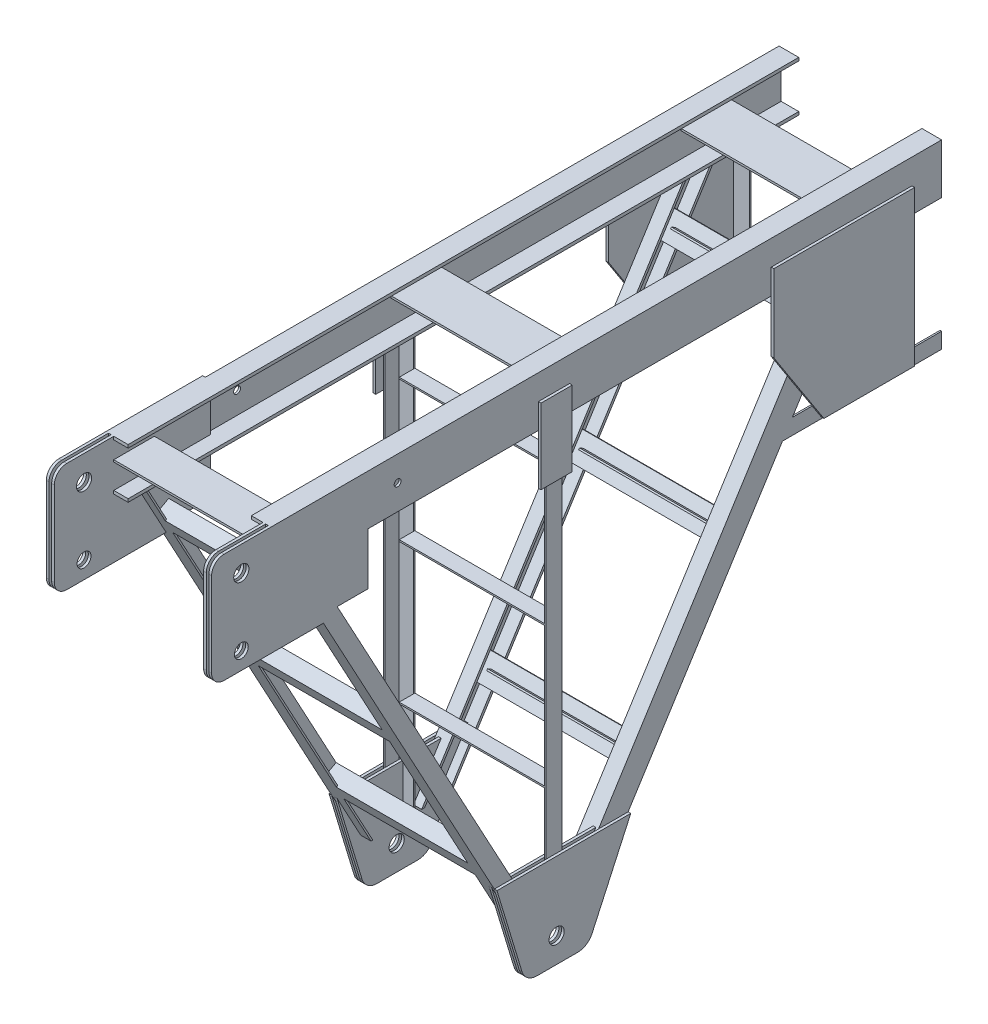
SolidWorks part; units mm, degrees
ref_plane "前视基准面" through (0, 0, 0) normal (0, 0, 1) x (1, 0, 0)
ref_plane "上视基准面" through (0, 0, 0) normal (0, 1, 0) x (1, 0, 0)
ref_plane "右视基准面" through (0, 0, 0) normal (1, 0, 0) x (0, 0, -1)
sketch "草图2" plane through (0, 0, 0) normal (0, 0, 1) x (1, 0, 0)
  line L0 (0, 0) -> (0, 160)
  line L1 (0, 160) -> (63, 160)
  line L2 (63, 160) -> (63, 150)
  line L3 (63, 150) -> (6.5, 150)
  line L4 (6.5, 150) -> (6.5, 10)
  line L5 (6.5, 10) -> (63, 10)
  line L6 (63, 10) -> (63, 0)
  line L7 (63, 0) -> (0, 0)
  line L8 (457, 160) -> (520, 160)
  line L9 (520, 160) -> (520, 0)
  line L10 (520, 0) -> (457, 0)
  line L11 (457, 0) -> (457, 10)
  line L12 (457, 10) -> (513.5, 10)
  line L13 (513.5, 10) -> (513.5, 150)
  line L14 (513.5, 150) -> (457, 150)
  line L15 (457, 150) -> (457, 160)
  dimension "D1" = 160
  dimension "D2" = 10
  dimension "D3" = 6.5
  dimension "D4" = 63
  dimension "D5" = 520
extrude "拉伸1" add sketch "草图2" along normal blind 2335
sketch "草图5" plane through (0, 0, 0) normal (-1, 0, 0) x (0, 0, 1)
  line L0 (160, 95) -> (320, 95)
  line L1 (320, 95) -> (320, 88.5)
  line L2 (243.25, 88.5) -> (320, 88.5)
  line L3 (243.25, 88.5) -> (243.25, 48.5)
  line L4 (243.25, 48.5) -> (236.75, 48.5)
  line L5 (236.75, 48.5) -> (236.75, 88.5)
  line L6 (236.75, 88.5) -> (160, 88.5)
  line L7 (160, 88.5) -> (160, 95)
  line L8 (0, 160) -> (0, 0) construction
  point P10 (0, 80)
  dimension "D1" = 160
  dimension "D2" = 6.5
  dimension "D3" = 6.5
  dimension "D4" = 40
  dimension "D5" = 160
  dimension "D6" = 15
extrude "拉伸3" add sketch "草图5" against normal blind 511.5
sketch "草图11" plane through (0, 0, 0) normal (-1, 0, 0) x (0, 0, 1)
  line L0 (2335, 160) -> (2335, 0) construction
  line L1 (2335, 80) -> (0, 80) construction
  line L2 (0, 160) -> (0, 0) construction
  circle A0 centre (2240, 80) radius 24.25
  dimension "D1" = 48.5
  dimension "D2" = 95
extrude "拉伸10" cut sketch "草图11" against normal through all
pattern_linear "阵列(线性)1" count 3 spacing 927.5 along (0, 0, 1) of "拉伸3"
sketch "草图12" plane through (0, 0, 0) normal (-1, 0, 0) x (0, 0, 1)
  line L0 (2240, 80) -> (0, 80) construction
  line L1 (0, 160) -> (0, 0) construction
  line L2 (1240, 80) -> (1240, -1500) construction
  line L3 (2095, 80) -> (1240, -1500) construction
  line L4 (1240, -1500) -> (240, 80) construction
  line L5 (2335, 10) -> (2335, 150) construction
  line L6 (243.2945, 0) -> (1192.6616, -1500)
  line L7 (2335, 0) -> (0, 0) construction
  line L8 (1192.6616, -1500) -> (1268.4257, -1500)
  line L9 (1268.4257, -1500) -> (2080.1345, 0)
  line L10 (2080.1345, 0) -> (2023.2832, 0)
  line L11 (2023.2832, 0) -> (1265, -1401.2718)
  line L12 (1265, -1401.2718) -> (1265, 0)
  line L13 (1265, 0) -> (1215, 0)
  line L14 (1215, 0) -> (1215, -1385.7053)
  line L15 (1215, -1385.7053) -> (337.9713, 0)
  line L16 (337.9713, 0) -> (243.2945, 0)
  point P9 (2335, 80)
  dimension "D2" = 240
  dimension "D3" = 240
  dimension "D4" = 1000
  dimension "D5" = 40
  dimension "D6" = 80
  dimension "D7" = 50
  dimension "D8" = 25
  dimension "D9" = 25
  dimension "D10" = 50
  dimension "D11" = 1580
extrude "拉伸11" add sketch "草图12" against normal blind 50
pattern_linear "阵列(线性)2" count 2 spacing 470 along (1, 0, 0) of "拉伸11"
sketch "草图15" plane through (50, 0, 0) normal (1, 0, 0) x (0, 0, -1)
  line L0 (-1265, 0) -> (-1220, 0)
  line L1 (-1265, 0) -> (-1215, 0) construction
  line L2 (-1220, 0) -> (-1220, -1500)
  line L3 (-1192.6616, -1500) -> (-1268.4257, -1500) construction
  line L4 (-1220, -1500) -> (-1262.7406, -1500)
  line L5 (-1262.7406, -1500) -> (-2074.4494, 0)
  line L6 (-2080.1345, 0) -> (-2023.2832, 0) construction
  line L7 (-2074.4494, 0) -> (-2023.2832, 0)
  line L8 (-2023.2832, 0) -> (-1265, -1401.2718)
  line L9 (-1265, -1401.2718) -> (-1265, 0)
  line L10 (-1215, 0) -> (-1215, -1385.7053) construction
  line L11 (-1268.4257, -1500) -> (-2080.1345, 0) construction
  dimension "D1" = 5
  dimension "D2" = 5
extrude "拉伸12" cut sketch "草图15" against normal blind 45
sketch "草图16" plane through (50, 0, 0) normal (1, 0, 0) x (0, 0, -1)
  line L0 (-337.9713, 0) -> (-243.2945, 0)
  line L1 (-243.2945, 0) -> (-1192.6616, -1500)
  line L2 (-1192.6616, -1500) -> (-1215, -1500)
  line L3 (-1192.6616, -1500) -> (-1220, -1500) construction
  line L4 (-1215, -1500) -> (-1215, -1385.7053)
  line L5 (-1215, -1385.7053) -> (-337.9713, 0)
  line L6 (-1220, -1500) -> (-1220, 0) construction
extrude "拉伸13" cut sketch "草图16" against normal blind 7
sketch "草图17" plane through (43, 0, 0) normal (1, 0, 0) x (0, 0, -1)
  line L0 (-1202.1293, -1500) -> (-1215, -1500)
  line L1 (-1215, -1500) -> (-1192.6616, -1500) construction
  line L2 (-1215, -1500) -> (-1215, -1400.6643)
  line L3 (-1215, -1400.6643) -> (-328.5036, 0)
  line L4 (-328.5036, 0) -> (-252.7622, 0)
  line L5 (-243.2945, 0) -> (-337.9713, 0) construction
  line L6 (-252.7622, 0) -> (-1202.1293, -1500)
  line L7 (-1192.6616, -1500) -> (-243.2945, 0) construction
  line L8 (-337.9713, 0) -> (-1215, -1385.7053) construction
  dimension "D1" = 8
  dimension "D2" = 8
extrude "拉伸14" cut sketch "草图17" against normal blind 38
sketch "草图18" plane through (470, 0, 0) normal (-1, 0, 0) x (0, 0, 1)
  line L0 (2074.4494, 0) -> (2023.2832, 0)
  line L1 (2023.2832, 0) -> (1265, -1401.2718) construction
  line L2 (2023.2832, 0) -> (1265, -1401.2718)
  line L3 (1265, -1401.2718) -> (1265, 0)
  line L4 (1265, 0) -> (1220, 0)
  line L6 (1220, 0) -> (1220, -1500)
  line L7 (1192.6616, -1500) -> (1268.4257, -1500) construction
  line L8 (1220, -1500) -> (1262.7406, -1500)
  line L9 (1262.7406, -1500) -> (2074.4494, 0)
  line L10 (1268.4257, -1500) -> (2080.1345, 0) construction
  line L11 (1215, 0) -> (1215, -1385.7053) construction
  line L12 (2023.2832, 0) -> (1265, 0) construction
  line L13 (2335, 0) -> (2080.1345, 0) construction
  dimension "D1" = 5
  dimension "D2" = 5
extrude "拉伸15" cut sketch "草图18" against normal blind 45
sketch "草图19" plane through (470, 0, 0) normal (-1, 0, 0) x (0, 0, 1)
  line L0 (252.7622, 0) -> (328.5036, 0)
  line L1 (328.5036, 0) -> (1215, -1400.6643)
  line L2 (1215, -1400.6643) -> (1215, -1500)
  line L3 (1192.6616, -1500) -> (1220, -1500) construction
  line L4 (1215, -1500) -> (1202.1293, -1500)
  line L5 (1202.1293, -1500) -> (252.7622, 0)
  line L6 (1220, 0) -> (1220, -1500) construction
  line L7 (1215, 0) -> (337.9713, 0) construction
  line L8 (1215, -1385.7053) -> (337.9713, 0) construction
  line L9 (243.2945, 0) -> (1192.6616, -1500) construction
  line L12 (1215, 0) -> (1215, -1385.7053) construction
  dimension "D1" = 8
  dimension "D2" = 8
extrude "拉伸16" cut sketch "草图19" against normal blind 2
sketch "草图20" plane through (472, 0, 0) normal (-1, 0, 0) x (0, 0, 1)
  line L0 (253.3539, 0) -> (327.9119, 0)
  line L1 (1192.6616, -1500) -> (1268.4257, -1500) construction
  line L2 (327.9119, 0) -> (1215, -1401.5992)
  line L3 (1215, -1401.5992) -> (1215, -1500)
  line L4 (1215, -1500) -> (1202.721, -1500)
  line L6 (1202.721, -1500) -> (253.3539, 0)
  line L7 (1215, -1385.7053) -> (337.9713, 0) construction
  line L9 (1215, 0) -> (337.9713, 0) construction
  line L10 (243.2945, 0) -> (1192.6616, -1500) construction
  line L11 (1215, 0) -> (1215, -1385.7053) construction
  dimension "D1" = 8.5
  dimension "D2" = 8.5
extrude "拉伸17" cut sketch "草图20" against normal blind 42.7
sketch "草图21" plane through (520, 0, 0) normal (1, 0, 0) x (0, 0, -1)
  line L0 (-1265, -1401.2718) -> (-1265, 0) construction
  line L1 (-1265, -100) -> (-1215, -100)
  line L2 (-1265, -100) -> (-1265, -150)
  line L3 (-1265, -150) -> (-1215, -150)
  line L4 (-1215, -100) -> (-1215, -150)
  line L5 (-1215, 0) -> (-1215, -1385.7053) construction
  line L6 (-2335, 0) -> (-2080.1345, 0) construction
  dimension "D1" = 50
  dimension "D2" = 100
extrude "拉伸18" add sketch "草图21" against normal blind 470
pattern_linear "阵列(线性)3" count 3 spacing 450 along (0, -1, 0) of "拉伸18"
sketch "草图25" plane through (0, 0, 1265) normal (0, 0, 1) x (1, 0, 0)
  line L0 (50, -150) -> (515, -150) construction
  line L1 (5, -105) -> (515, -105)
  line L2 (5, -105) -> (5, -150)
  line L3 (5, -150) -> (515, -150)
  line L4 (515, -105) -> (515, -150)
  line L5 (50, -100) -> (515, -100) construction
  line L6 (5, 0) -> (5, -1401.2718) construction
  line L7 (515, -550) -> (515, -150) construction
  line L8 (50, -600) -> (515, -600) construction
  line L9 (515, -1000) -> (515, -600) construction
  line L10 (5, -600) -> (515, -600)
  line L11 (5, -600) -> (5, -555)
  line L12 (5, -555) -> (515, -555)
  line L13 (515, -600) -> (515, -555)
  line L14 (50, -550) -> (515, -550) construction
  line L15 (515, -1401.2718) -> (515, -1050) construction
  line L16 (5, -1050) -> (515, -1050)
  line L17 (5, -1050) -> (5, -1005)
  line L18 (5, -1005) -> (515, -1005)
  line L19 (515, -1050) -> (515, -1005)
  line L20 (50, -1000) -> (515, -1000) construction
  line L21 (5, 0) -> (5, -1401.2718) construction
  line L22 (50, -600) -> (515, -600) construction
  line L23 (50, -1050) -> (515, -1050) construction
  dimension "D1" = 5
  dimension "D2" = 5
  dimension "D3" = 5
extrude "拉伸19" cut sketch "草图25" against normal blind 45
sketch "草图26" plane through (520, 0, 0) normal (1, 0, 0) x (0, 0, -1)
  line L0 (-1969.1692, -100) -> (-2013.1436, -123.7962)
  line L1 (-1969.1692, -100) -> (-1945.373, -143.9743)
  line L2 (-2013.1436, -123.7962) -> (-1989.3473, -167.7705)
  line L3 (-1945.373, -143.9743) -> (-1989.3473, -167.7705)
  line L4 (-2023.2832, 0) -> (-1265, -1401.2718) construction
  line L5 (-1268.4257, -1500) -> (-2080.1345, 0) construction
  line L6 (-2335, 0) -> (-2080.1345, 0) construction
  dimension "D1" = 50
  dimension "D2" = 100
extrude "拉伸20" add sketch "草图26" against normal blind 520
pattern_linear "阵列(线性)4" count 3 spacing 575 along (0, -0.8795, -0.4759) of "拉伸20"
sketch "草图27" plane through (0, -846.8836, 1565.0012) normal (0, 0.4759, -0.8795) x (-1, 0, 0)
  line L0 (-5, -630.3547) -> (-5, -350.7728) construction
  line L1 (-515, 799.2272) -> (-5, 799.2272)
  line L2 (-515, 799.2272) -> (-515, 844.2272)
  line L3 (-515, 844.2272) -> (-5, 844.2272)
  line L4 (-5, 799.2272) -> (-5, 844.2272)
  line L5 (-5, 224.2272) -> (-515, 224.2272)
  line L6 (-5, 224.2272) -> (-5, 269.2272)
  line L7 (-5, 269.2272) -> (-515, 269.2272)
  line L8 (-515, 224.2272) -> (-515, 269.2272)
  line L9 (-515, -350.7728) -> (-5, -350.7728)
  line L10 (-515, -350.7728) -> (-515, -305.7728)
  line L11 (-515, -305.7728) -> (-5, -305.7728)
  line L12 (-5, -350.7728) -> (-5, -305.7728)
  line L13 (-5, -300.7728) -> (-515, -300.7728) construction
  line L14 (-5, 274.2272) -> (-515, 274.2272) construction
  line L15 (-515, 224.2272) -> (-515, -300.7728) construction
  line L16 (-5, 274.2272) -> (-5, 799.2272) construction
  line L17 (-5, 849.2272) -> (-515, 849.2272) construction
  line L18 (-5, 799.2272) -> (-515, 799.2272) construction
  dimension "D1" = 5
  dimension "D2" = 5
  dimension "D3" = 5
extrude "拉伸21" cut sketch "草图27" against normal blind 45
sketch "草图29" plane through (0, 0, 0) normal (-1, 0, 0) x (0, 0, 1)
  line L0 (356.8827, -100) -> (399.6665, -167.5984)
  line L1 (356.8827, -100) -> (352.6578, -102.674)
  line L2 (399.6665, -167.5984) -> (395.4416, -170.2724)
  line L3 (352.6578, -102.674) -> (395.4416, -170.2724)
  line L4 (1215, -1385.7053) -> (337.9713, 0) construction
  line L5 (1215, 0) -> (337.9713, 0) construction
  line L6 (1215, -1385.7053) -> (1147.4016, -1428.4892) construction
  line L7 (243.2945, 0) -> (1192.6616, -1500) construction
  line L8 (337.9713, 0) -> (270.3729, -42.7838) construction
  line L9 (304.1721, -21.3919) -> (1181.2008, -1407.0973) construction
  dimension "D1" = 100
  dimension "D2" = 2.5
  dimension "D3" = 80
  dimension "D4" = 2.5
extrude "拉伸22" add sketch "草图29" against normal blind 520
sketch "草图30" plane through (0, 132.6721, 209.6219) normal (0, 0.5348, 0.845) x (1, 0, 0)
  line L0 (514.7, -315.358) -> (5, -315.358) construction
  line L1 (45.35, -312.858) -> (474.35, -312.858)
  line L2 (45.35, -312.858) -> (45.35, -317.858)
  line L3 (45.35, -317.858) -> (474.35, -317.858)
  line L4 (474.35, -312.858) -> (474.35, -317.858)
  line L6 (5, -355.358) -> (5, -275.358) construction
  line L7 (45.35, -312.858) -> (5, -315.358) construction
  line L8 (45.35, -317.858) -> (5, -315.358) construction
  line L9 (474.35, -312.858) -> (514.7, -315.358) construction
  line L10 (474.35, -317.858) -> (514.7, -315.358) construction
  line L14 (514.7, -275.358) -> (514.7, -355.358) construction
  dimension "D1" = 429
  dimension "D2" = 5
extrude "拉伸23" add sketch "草图30" along normal blind 15
pattern_linear "阵列(线性)5" count 3 spacing 550 along (0, -0.845, 0.5348) of "拉伸22", "拉伸23"
sketch "草图31" plane through (520, 0, 0) normal (1, 0, 0) x (0, 0, -1)
  line L1 (-1430.7675, -1200) -> (-1002.7882, -1200)
  line L2 (-1430.7675, -1200) -> (-1340, -1500)
  line L3 (-1340, -1500) -> (-1140, -1500)
  line L4 (-1002.7882, -1200) -> (-1140, -1500)
  line L5 (-1268.4257, -1500) -> (-2080.1345, 0) construction
  line L6 (-243.2945, 0) -> (-1192.6616, -1500) construction
  line L9 (-1265, 0) -> (-1340, -1500) construction
  line L10 (-1140, -1500) -> (-1215, 0) construction
  line L11 (-1192.6616, -1500) -> (-1268.4257, -1500) construction
  dimension "D1" = 200
  dimension "D3" = 300
extrude "拉伸24" add sketch "草图31" along normal blind 8.5
pattern_linear "阵列(线性)6" count 2 spacing 17 along (-1, 0, 0) of "拉伸24"
pattern_linear "阵列(线性)7" count 2 spacing 511.5 along (-1, 0, 0) of "拉伸24", "阵列(线性)6"
sketch "草图33" plane through (0, -1500, 0) normal (0, -1, 0) x (1, 0, 0)
  line L0 (503, 1241.3703) -> (17, 1241.3703) construction
  line L1 (503, 1262.7406) -> (503, 1220) construction
  line L2 (17, 1262.7406) -> (17, 1220) construction
  line L3 (520, 1002.7882) -> (520, 1192.6616) construction
  line L4 (520, 1041.3703) -> (511.5, 1041.3703)
  line L5 (520, 1041.3703) -> (520, 1441.3703)
  line L6 (520, 1441.3703) -> (511.5, 1441.3703)
  line L7 (511.5, 1041.3703) -> (511.5, 1441.3703)
  line L8 (511.5, 1192.6616) -> (511.5, 1140) construction
  line L10 (8.5, 1041.3703) -> (0, 1041.3703)
  line L11 (8.5, 1041.3703) -> (8.5, 1441.3703)
  line L12 (8.5, 1441.3703) -> (0, 1441.3703)
  line L13 (0, 1041.3703) -> (0, 1441.3703)
  line L15 (8.5, 1262.7406) -> (8.5, 1220) construction
  line L16 (0, 1340) -> (0, 1268.4257) construction
  dimension "D1" = 200
  dimension "D2" = 200
  dimension "D3" = 200
  dimension "D4" = 200
extrude "拉伸26" cut sketch "草图33" against normal blind 160
fillet "圆角1" radius 50 10 edges at (524.25, -1500, 1340) (524.25, -1500, 1140) (507.25, -1500, 1340) (507.25, -1500, 1140) (12.75, -1500, 1340) (12.75, -1500, 1140) (-4.25, -1500, 1340) (-4.25, -1500, 1140)
sketch "草图35" plane through (-8.5, 0, 0) normal (-1, 0, 0) x (0, 0, 1)
  circle A0 centre (1240, -1420) radius 24.25
  circle A1 centre (2240, 80) radius 24.25 construction
  dimension "D3" = 48.5
  dimension "D1" = 1500
  dimension "D2" = 1000
extrude "拉伸27" cut sketch "草图35" against normal through all
sketch "草图36" plane through (0, -1500, 0) normal (0, -1, 0) x (1, 0, 0)
  line L0 (503, 1262.7406) -> (503, 1220) construction
  line L1 (503, 1472.7406) -> (17, 1472.7406)
  line L2 (503, 1472.7406) -> (503, 972.7406)
  line L3 (503, 972.7406) -> (17, 972.7406)
  line L4 (17, 1472.7406) -> (17, 972.7406)
  line L5 (17, 1262.7406) -> (17, 1220) construction
  line L6 (503, 1262.7406) -> (470, 1262.7406) construction
  dimension "D1" = 500
  dimension "D2" = 210
extrude "拉伸28" cut sketch "草图36" against normal blind 160
sketch "草图37" plane through (0, 0, 2335) normal (0, 0, 1) x (1, 0, 0)
  line L0 (0, 160) -> (0, 0) construction
  line L1 (8.5, 160) -> (511.5, 160)
  line L2 (8.5, 160) -> (8.5, 0)
  line L3 (8.5, 0) -> (511.5, 0)
  line L4 (511.5, 160) -> (511.5, 0)
  line L5 (520, 0) -> (520, 160) construction
  line L6 (520, 160) -> (457, 160) construction
  line L7 (457, 0) -> (520, 0) construction
  dimension "D1" = 8.5
  dimension "D2" = 8.5
extrude "拉伸29" cut sketch "草图37" against normal blind 190
sketch "草图38" plane through (6.5, 0, 0) normal (1, 0, 0) x (0, 0, -1)
  line L0 (-2335, 150) -> (-1935, 150)
  line L1 (-2335, 150) -> (0, 150) construction
  line L2 (-1935, 150) -> (-1865, 80)
  line L3 (-1865, 80) -> (-1935, 10)
  line L4 (-1935, 10) -> (-2335, 10)
  line L5 (-2335, 10) -> (-2335, 150) construction
  line L6 (-2335, 10) -> (-2335, 150)
  line L7 (-2335, 10) -> (0, 10) construction
  line L8 (-1865, 80) -> (-2240, 80) construction
  line L9 (-1935, 150) -> (-1935, 10) construction
  line L13 (-2015, 95) -> (-2015, 88.5) construction
  dimension "D1" = 80
extrude "拉伸30" add sketch "草图38" along normal blind 2
pattern_linear "阵列(线性)8" count 2 spacing 505 along (1, 0, 0) of "拉伸30"
sketch "草图39" plane through (0, 0, 0) normal (-1, 0, 0) x (0, 0, 1)
  line L0 (1835, -166.2038) -> (1933.3438, -166.2038)
  line L1 (2335, 160) -> (1835, 160)
  line L2 (2335, 160) -> (2335, -190)
  line L3 (2335, -190) -> (1977.3181, -190)
  line L4 (1430.7675, -1200) -> (2080.1345, 0) construction
  line L5 (2023.2832, 0) -> (1373.9161, -1200) construction
  line L6 (2335, 160) -> (0, 160) construction
  line L7 (1933.3438, -166.2038) -> (1977.3181, -190)
  line L9 (1835, 160) -> (1835, -166.2038)
  dimension "D1" = 350
  dimension "D2" = 500
extrude "拉伸31" add sketch "草图39" along normal blind 8.5
pattern_linear "阵列(线性)9" count 2 spacing 17 along (1, 0, 0) of "拉伸31"
sketch "草图40" plane through (-8.5, 0, 0) normal (-1, 0, 0) x (0, 0, 1)
  line L0 (2240, 160) -> (2240, -190) construction
  line L1 (2335, 160) -> (1835, 160) construction
  line L3 (2335, -190) -> (2335, 160) construction
  line L4 (1977.3181, -190) -> (2335, -190) construction
  circle A0 centre (2240, 80) radius 24.25
  dimension "D2" = 48.5
  dimension "D1" = 95
  dimension "D3" = 80
extrude "拉伸32" cut sketch "草图40" against normal through all
sketch "草图41" plane through (0, 0, 2335) normal (0, 0, 1) x (1, 0, 0)
  line L0 (17, 160) -> (-8.5, 160) construction
  line L1 (8.5, 0) -> (0, 0)
  line L2 (8.5, 0) -> (8.5, 160)
  line L3 (8.5, 160) -> (0, 160)
  line L4 (0, 0) -> (0, 160)
  line L5 (0, -190) -> (0, 0) construction
extrude "拉伸33" cut sketch "草图41" against normal blind 190
sketch "草图42" plane through (6.5, 0, 0) normal (1, 0, 0) x (0, 0, -1)
  line L0 (-1935, 150) -> (0, 150) construction
  line L1 (-1935, 150) -> (-1835, 150)
  line L2 (-1935, 150) -> (-1935, 10)
  line L3 (-1935, 10) -> (-1835, 10)
  line L4 (-1835, 150) -> (-1835, 10)
  line L5 (-1935, 10) -> (0, 10) construction
  line L6 (-1835, 150) -> (-1835, 10) construction
  dimension "D1" = 100
extrude "拉伸34" add sketch "草图42" along normal blind 2
sketch "草图48" plane through (0, 0, 0) normal (-1, 0, 0) x (0, 0, 1)
  line L0 (243.2945, 0) -> (0, 0) construction
  line L1 (95, 0) -> (145, 0)
  line L2 (95, 0) -> (95, -370)
  line L3 (95, -370) -> (145, -370)
  line L4 (145, 0) -> (145, -370)
  line L5 (0, 160) -> (0, 0) construction
  dimension "D1" = 50
  dimension "D2" = 370
  dimension "D3" = 95
extrude "拉伸40" add sketch "草图48" against normal blind 520 separate body
sketch "草图49" plane through (0, -370, 0) normal (0, -1, 0) x (1, 0, 0)
  line L0 (5, 95) -> (5, 140)
  line L1 (520, 95) -> (0, 95) construction
  line L2 (5, 140) -> (50, 140)
  line L3 (50, 140) -> (50, 145)
  line L4 (520, 145) -> (0, 145) construction
  line L5 (50, 145) -> (470, 145)
  line L6 (470, 145) -> (470, 140)
  line L7 (470, 140) -> (515, 140)
  line L8 (515, 140) -> (515, 95)
  line L9 (515, 95) -> (5, 95)
  line L10 (0, 95) -> (0, 145) construction
  line L11 (520, 95) -> (520, 145) construction
  dimension "D1" = 5
  dimension "D2" = 5
  dimension "D3" = 50
  dimension "D4" = 5
extrude "拉伸41" cut sketch "草图49" against normal blind 370
sketch "草图50" plane through (0, 0, 0) normal (-1, 0, 0) x (0, 0, 1)
  line L0 (95, -370) -> (145, -370) construction
  line L1 (0, -370) -> (477.4717, -370)
  line L2 (0, -370) -> (0, -420)
  line L3 (0, -420) -> (509.1173, -420)
  line L4 (477.4717, -370) -> (509.1173, -420)
  line L5 (243.2945, 0) -> (1002.7882, -1200) construction
  line L7 (0, 160) -> (0, 0) construction
  dimension "D1" = 50
extrude "拉伸42" add sketch "草图50" against normal blind 50
pattern_linear "阵列(线性)10" count 2 spacing 470 along (1, 0, 0) of "拉伸42"
sketch "草图51" plane through (50, 0, 0) normal (1, 0, 0) x (0, 0, -1)
  line L0 (0, -370) -> (0, -420) construction
  line L1 (-140, -370) -> (0, -370)
  line L2 (-140, -370) -> (-140, -415)
  line L3 (-140, -415) -> (0, -415)
  line L4 (0, -370) -> (0, -415)
  line L5 (0, -420) -> (-509.1173, -420) construction
  line L6 (-505.9528, -415) -> (-477.4717, -370)
  line L7 (-509.1173, -420) -> (-477.4717, -370) construction
  line L8 (-477.4717, -370) -> (-145, -370)
  line L9 (-477.4717, -370) -> (-145, -370) construction
  line L10 (-145, -370) -> (-145, -415)
  line L11 (-145, -415) -> (-505.9528, -415)
  line L12 (-145, 0) -> (-145, -370) construction
  dimension "D1" = 5
extrude "拉伸43" cut sketch "草图51" against normal blind 45
sketch "草图52" plane through (470, 0, 0) normal (-1, 0, 0) x (0, 0, 1)
  line L0 (0, -370) -> (0, -420) construction
  line L1 (140, -370) -> (0, -370)
  line L2 (140, -370) -> (140, -415)
  line L3 (140, -415) -> (0, -415)
  line L4 (0, -370) -> (0, -415)
  line L5 (0, -420) -> (509.1173, -420) construction
  line L6 (145, -370) -> (145, -415)
  line L7 (145, -415) -> (505.9528, -415)
  line L9 (505.9528, -415) -> (477.4717, -370)
  line L10 (477.4717, -370) -> (145, -370)
  line L11 (243.2945, 0) -> (477.4717, -370) construction
  dimension "D1" = 5
extrude "拉伸44" cut sketch "草图52" against normal blind 45
sketch "草图53" plane through (50, 0, 0) normal (1, 0, 0) x (0, 0, -1)
  line L0 (-145, -370) -> (-145, -420)
  line L1 (-145, 0) -> (-145, -415) construction
  line L2 (0, -420) -> (-509.1173, -420) construction
  line L3 (-145, -420) -> (-95, -420)
  line L4 (-95, -420) -> (-95, -415)
  line L5 (-140, -415) -> (0, -415) construction
  line L6 (-95, -415) -> (-140, -415)
  line L7 (-140, -415) -> (-140, -370)
  line L8 (-140, 0) -> (-140, -415) construction
  line L9 (-140, -370) -> (-145, -370)
  dimension "D1" = 50
  dimension "D2" = 50
extrude "拉伸45" add sketch "草图53" along normal blind 428.5
sketch "草图55" plane through (0, 0, 0) normal (-1, 0, 0) x (0, 0, 1)
  line L0 (0, 80) -> (1835, 80) construction
  line L1 (0, 160) -> (0, 0) construction
  line L2 (1835, 160) -> (1835, 0) construction
  line L3 (0, -420) -> (509.1173, -420) construction
  line L6 (95, 80) -> (95, -415)
  line L7 (95, -415) -> (385, -415)
  line L8 (385, -415) -> (545, -167.5)
  line L9 (545, -167.5) -> (545, 80)
  line L10 (545, 80) -> (95, 80)
  line L12 (95, -167.5) -> (545, -167.5) construction
  dimension "D1" = 95
  dimension "D2" = 290
  dimension "D3" = 450
  dimension "D4" = 5
extrude "拉伸46" add sketch "草图55" along normal blind 8.5
pattern_linear "阵列(线性)11" count 2 spacing 528.5 along (1, 0, 0) of "拉伸46"
sketch "草图57" plane through (0, 0, 0) normal (-1, 0, 0) x (0, 0, 1)
  line L0 (1215, 0) -> (1215, -1200) construction
  line L1 (1190, 80) -> (1290, 80)
  line L2 (1190, 80) -> (1190, -160)
  line L3 (1190, -160) -> (1290, -160)
  line L4 (1290, 80) -> (1290, -160)
  line L6 (1835, 0) -> (1265, 0) construction
  dimension "D1" = 100
  dimension "D2" = 25
  dimension "D3" = 80
  dimension "D4" = 160
extrude "拉伸48" add sketch "草图57" along normal blind 8.5
pattern_linear "阵列(线性)12" count 2 spacing 528.5 along (1, 0, 0) of "拉伸48"
pattern_linear "阵列(线性)13" count 2 spacing 520 along (1, 0, 0) of "拉伸31"
pattern_linear "阵列(线性)14" count 2 spacing 503 along (1, 0, 0) of "拉伸31"
sketch "草图58" plane through (520, 0, 0) normal (1, 0, 0) x (0, 0, -1)
  line L0 (-2335, -190) -> (-2335, 160) construction
  line L1 (-2335, 160) -> (0, 160) construction
  circle A0 centre (-2240, 80) radius 24.25
  circle A1 centre (-2240, -135) radius 22.25
  dimension "D1" = 48.5
  dimension "D2" = 44.5
  dimension "D3" = 95
  dimension "D4" = 80
  dimension "D5" = 95
  dimension "D6" = 215
extrude "拉伸49" cut sketch "草图58" against normal through all
fillet "圆角2" radius 40 8 edges at (515.75, 160, 2335) (12.75, 160, 2335) (12.75, -190, 2335) (515.75, -190, 2335) (498.75, -190, 2335) (498.75, 160, 2335) (-4.25, 160, 2335) (-4.25, -190, 2335)
sketch "草图59" plane through (520, 0, 0) normal (1, 0, 0) x (0, 0, -1)
  line L0 (-2240, 80) -> (0, 80) construction
  line L1 (0, 0) -> (0, 160) construction
  circle A0 centre (-1740, 80) radius 11
  dimension "D1" = 22
  dimension "D2" = 500
extrude "拉伸50" cut sketch "草图59" against normal through all
